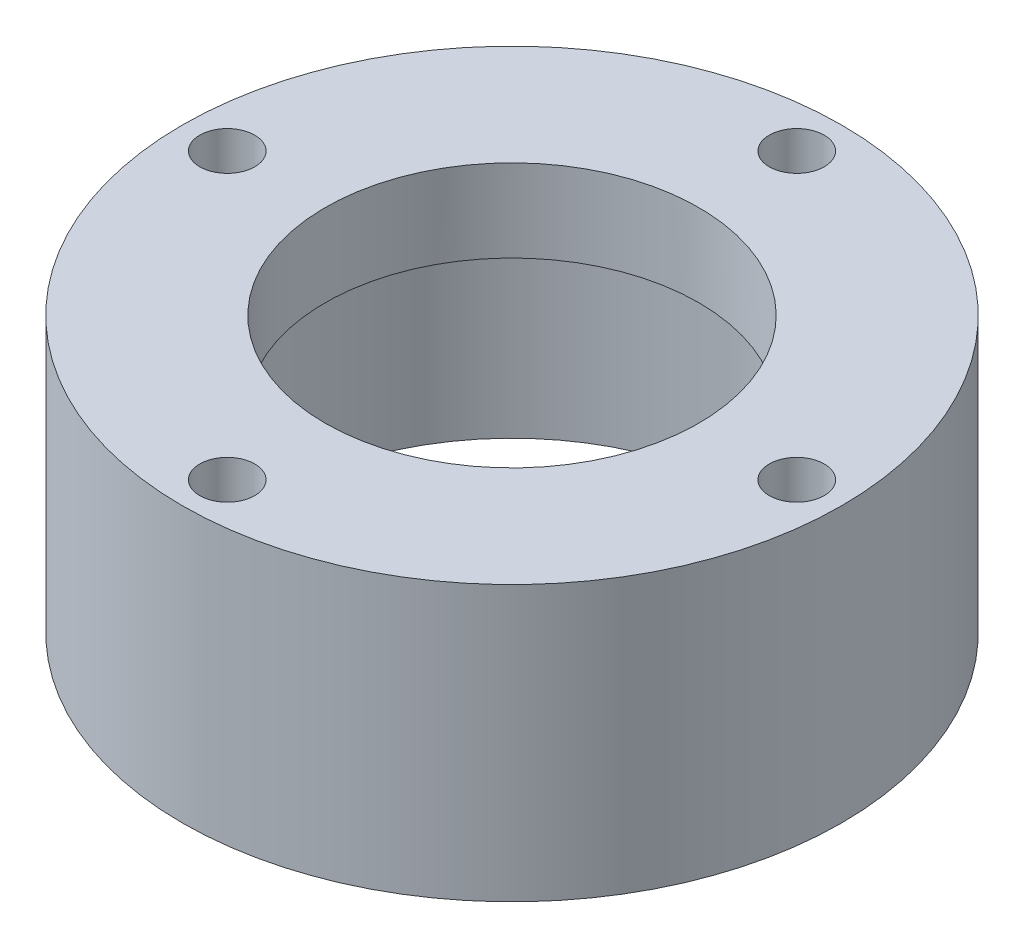
SolidWorks part; units mm, degrees
ref_plane "Спереди" through (0, 0, 0) normal (0, 0, 1) x (1, 0, 0)
ref_plane "Сверху" through (0, 0, 0) normal (0, 1, 0) x (1, 0, 0)
ref_plane "Справа" through (0, 0, 0) normal (1, 0, 0) x (0, 0, -1)
sketch "Эскиз1" plane through (0, 0, 0) normal (0, 1, 0) x (1, 0, 0)
  circle A0 centre (0, -1.754) radius 18
extrude "Вытянуть1" add sketch "Эскиз1" along normal blind 15 from offset 2
sketch "Эскиз2" plane through (0, -2, 0) normal (0, -1, 0) x (1, 0, 0)
  circle A0 centre (0, 1.754) radius 13
extrude "Вырез-Вытянуть1" cut sketch "Эскиз2" against normal blind 10.5
sketch "Эскиз3" plane through (0, 13, 0) normal (0, 1, 0) x (1, 0, 0)
  circle A0 centre (0, -1.754) radius 10.2
extrude "Вырез-Вытянуть2" cut sketch "Эскиз3" against normal through all
sketch "Эскиз4" plane through (0, 13, 0) normal (0, 1, 0) x (1, 0, 0)
  line L0 (18, -1.754) -> (31.4373, -1.754) construction
  line L1 (0, 16.246) -> (0, 21.1326) construction
  circle A0 centre (0, 13.7919) radius 1.5
  circle A1 centre (15.5459, -1.754) radius 1.5
  circle A2 centre (0, -17.2999) radius 1.5
  circle A3 centre (-15.5459, -1.754) radius 1.5
extrude "Вытянуть2" cut sketch "Эскиз4" against normal through all
